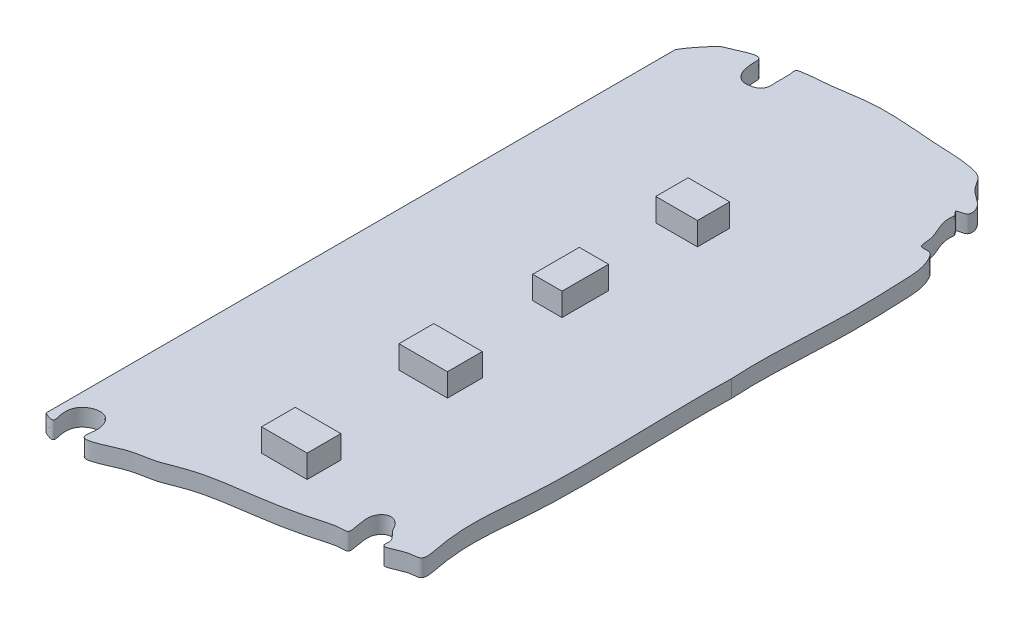
SolidWorks part; units mm, degrees
ref_plane "前视基准面" through (0, 0, 0) normal (0, 0, 1) x (1, 0, 0)
ref_plane "上视基准面" through (0, 0, 0) normal (0, 1, 0) x (1, 0, 0)
ref_plane "右视基准面" through (0, 0, 0) normal (1, 0, 0) x (0, 0, -1)
other "Configuration Table"
sketch "草图1" plane through (0, 0, 0) normal (0, 1, 0) x (1, 0, 0)
  line L0 (203.5758, 850.9118) -> (1017.879, 850.9118) construction
  line L1 (0, 17.6629) -> (0, 72.6629)
  spline S0 degree 3 poles (0, 72.6629) (0.36, 73.3178) (0.9618, 74.0137) (1.6518, 74.866) (2.2237, 75.0784) (2.9638, 75.3855) (4.4479, 76.0954) (4.4049, 75.0206) (4.471, 74.4148) (4.6689, 73.6782) (5.2831, 73.1136) (5.9655, 73.1749) (6.5274, 73.309) (6.9586, 73.8399) (6.8468, 74.6209) (6.8837, 75.3629) (6.8792, 75.9296) (6.7614, 76.4004) (7.3434, 76.5101) (8.1708, 76.6319) (9.9261, 76.7229) (12.4153, 77.2525) (15.5618, 77.1924) (18.8807, 76.8523) (21.2837, 76.8553) (23.0789, 76.292) (23.6232, 74.7634) (25.2252, 74.318) (25.4003, 72.7917) (24.2245, 72.8014) (24.8176, 72.3876) (24.6486, 71.5631) (25.1167, 70.4627) (25.5427, 69.4821) (25.5204, 68.3085) (26.4442, 68.6132) (27.3584, 67.309) (27.4658, 64.5576) (27.6774, 58.6246) (27.1449, 53.6525) (27.362, 50.2102) knots 0 0 0 0 0.038765 0.048891 0.056214 0.069512 0.097007 0.10627 0.11655 0.130622 0.14516 0.155389 0.165093 0.174918 0.187715 0.204593 0.213302 0.21944 0.224948 0.238908 0.267154 0.314169 0.372988 0.430417 0.489044 0.498922 0.52584 0.563815 0.575679 0.588506 0.593943 0.602697 0.629615 0.653081 0.664122 0.677508 0.687634 0.740395 0.819448 1 1 1 1
  spline S1 degree 3 poles (27.362, 50.2102) (27.1875, 44.6272) (27.966, 34.897) (26.683, 27.3054) (27.6956, 22.8812) (26.1872, 23.0429) (24.6012, 21.913) (24.859, 23.2811) (24.0394, 23.7264) (23.7168, 24.6475) (22.7941, 25.0802) (21.7584, 24.0858) (22.1227, 23.0219) (22.2901, 21.7435) (21.4673, 21.8818) (18.3408, 20.9698) (15.4859, 20.5024) (11.0727, 19.9316) (8.25, 18.6466) (6.3199, 18.63) (3.1256, 16.7174) (3.5434, 18.5503) (3.4364, 19.3755) (2.7932, 20.1909) (1.6542, 20.163) (0.6733, 19.2964) (0.7452, 17.9913) (1.0688, 17.1505) (0, 17.6629) knots 0 0 0 0 0.284862 0.411163 0.432642 0.448073 0.475378 0.482251 0.502279 0.512331 0.528883 0.539745 0.572393 0.579266 0.591998 0.603783 0.697117 0.775566 0.802817 0.839092 0.884645 0.89726 0.912555 0.92513 0.942299 0.960055 0.981327 1 1 1 1
  dimension "D1" = 55
extrude "凸台-拉伸1" add sketch "草图1" along normal blind 1.5
sketch "草图2" plane through (0, 1.5, 0) normal (0, 1, 0) x (1, 0, 0)
  line L1 (12.2565, 61.5239) -> (15.8979, 61.5239)
  line L2 (12.2565, 61.5239) -> (12.2565, 58.7)
  line L3 (12.2565, 58.7) -> (15.8979, 58.7)
  line L4 (15.8979, 61.5239) -> (15.8979, 58.7)
  line L5 (12.7705, 51.504) -> (15.3308, 51.504)
  line L6 (12.7705, 51.504) -> (12.7705, 47.4336)
  line L7 (12.7705, 47.4336) -> (15.3308, 47.4336)
  line L8 (15.3308, 51.504) -> (15.3308, 47.4336)
  line L9 (12.1831, 39.3761) -> (16.419, 39.3761)
  line L10 (12.1831, 39.3761) -> (12.1831, 36.3293)
  line L11 (12.1831, 36.3293) -> (16.419, 36.3293)
  line L12 (16.419, 39.3761) -> (16.419, 36.3293)
  line L13 (12.4678, 26.9881) -> (16.4487, 26.9881)
  line L14 (12.4678, 26.9881) -> (12.4678, 24.0345)
  line L15 (12.4678, 24.0345) -> (16.4487, 24.0345)
  line L16 (16.4487, 26.9881) -> (16.4487, 24.0345)
extrude "凸台-拉伸2" add sketch "草图2" along normal blind 2
sketch "草图3" plane through (0, 0, 0) normal (0, -1, 0) x (-1, 0, 0)
  line L1 (-1.109, 65.1234) -> (-11.8364, 65.1234)
  line L2 (-1.109, 65.1234) -> (-1.109, 68.547)
  line L3 (-1.109, 68.547) -> (-11.8364, 68.547)
  line L4 (-11.8364, 65.1234) -> (-11.8364, 68.547)
  line L5 (-13.3199, 58.2761) -> (-16.7436, 58.2761)
  line L6 (-13.3199, 58.2761) -> (-13.3199, 72.1989)
  line L7 (-13.3199, 72.1989) -> (-16.7436, 72.1989)
  line L8 (-16.7436, 58.2761) -> (-16.7436, 72.1989)
  circle A0 centre (-8.5269, 54.1677) radius 4.9548
extrude "凸台-拉伸3" add sketch "草图3" along normal blind 2 contours A0 | L2 L1 L4 L3 | L6 L5 L8 L7
